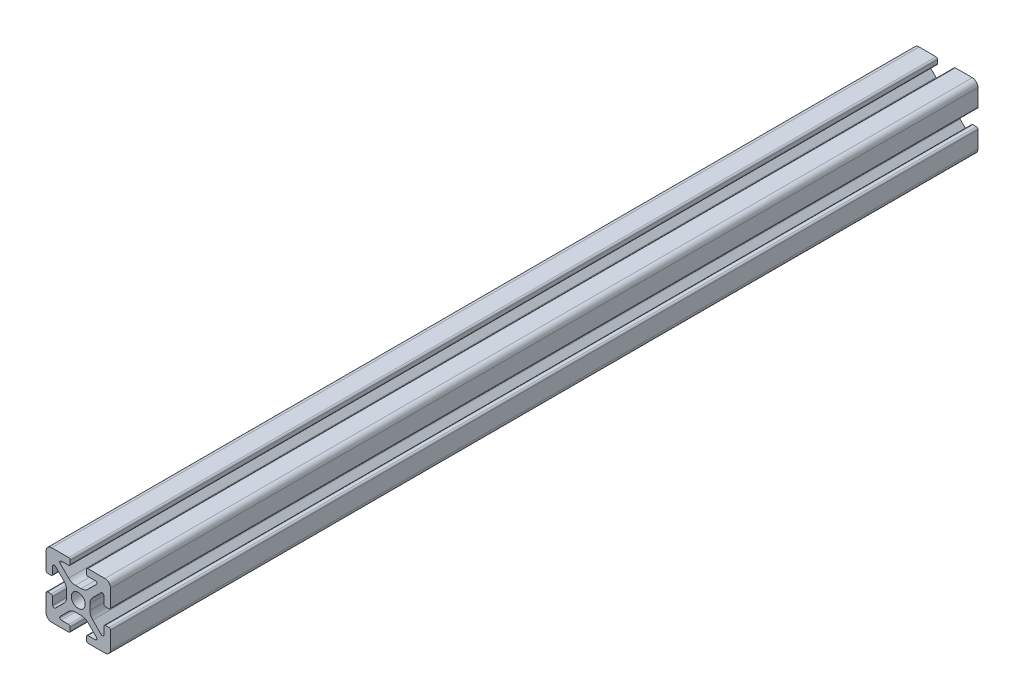
SolidWorks part; units mm, degrees
material "1060 Alloy"
ref_plane "Front Plane" through (0, 0, 0) normal (0, 0, 1) x (1, 0, 0)
ref_plane "Top Plane" through (0, 0, 0) normal (0, 1, 0) x (1, 0, 0)
ref_plane "Right Plane" through (0, 0, 0) normal (1, 0, 0) x (0, 0, -1)
sketch "Sketch2" plane through (0, 0, 0) normal (0, 0, 1) x (1, 0, 0)
  line L0 (0, 10) -> (0, -10) construction
  line L1 (-10, 0) -> (10, 0) construction
  line L2 (2.5, -10) -> (10, -10)
  line L3 (10, -10) -> (10, -2.5)
  line L4 (2.5, -10) -> (2.5, -7.9246)
  line L5 (2.5, -7.9246) -> (6.4571, -7.9246)
  line L6 (6.4571, -7.9246) -> (2.1325, -3.6)
  line L7 (0, 0) -> (10, -10) construction
  line L8 (10, -2.5) -> (7.9246, -2.5)
  line L9 (7.9246, -2.5) -> (7.9246, -6.4571)
  line L10 (7.9246, -6.4571) -> (3.6, -2.1325)
  line L11 (5.7623, -4.2948) -> (4.2948, -5.7623) construction
  circle A0 centre (0, 0) radius 2.15
  arc A1 (5.25, -7.9246) -> (5.6036, -7.0711) centre (5.25, -7.4246) ccw construction
  point P8 (0, -3.6)
  point P16 (5.0286, -5.0286)
  dimension "Center Hole Diameter" = 4.3
  dimension "D3" = 0.5
  dimension "Rail Height" = 20
  dimension "Rail Width" = 20
  dimension "T-Slot Width" = 5
  dimension "Slot Depth" = 6.4
  dimension "Slot Inner Width" = 11.5
sketch "Sketch3" plane through (0, 0, 0) normal (1, 0, 0) x (0, 0, -1)
  line L0 (-135.5, -10) -> (135.5, -10) construction
  line L1 (-110.1, 0) -> (110.1, 0) construction
  line L2 (0, 10) -> (0, -10) construction
  line L3 (0, 10) -> (0, -10) construction
  point P6 (-110.1, 0)
  point P8 (110.1, 0)
  dimension "Length" = 271
  dimension "D1" = 25.4
sketch "Sketch4" plane through (0, 0, 0) normal (0, 0, 1) x (1, 0, 0)
  line L0 (3, -10) -> (8.25, -10)
  line L1 (2.5, -10) -> (10, -10) construction
  line L2 (2.5, -10) -> (2.5, -7.9246) construction
  line L3 (2.5, -7.9246) -> (6.4571, -7.9246) construction
  line L4 (2.5, -8.4246) -> (2.5, -9.5)
  line L5 (3, -7.9246) -> (5.25, -7.9246)
  line L6 (0, -3.6) -> (0.8898, -3.6)
  line L7 (6.4571, -7.9246) -> (2.1325, -3.6) construction
  line L8 (3.0112, -4.4787) -> (5.6036, -7.0711)
  line L9 (10, -10) -> (10, -2.5) construction
  line L10 (7.9246, -6.4571) -> (3.6, -2.1325) construction
  line L11 (7.9246, -2.5) -> (7.9246, -6.4571) construction
  line L12 (7.9246, -5.25) -> (7.9246, -3)
  line L13 (10, -2.5) -> (7.9246, -2.5) construction
  line L14 (8.4246, -2.5) -> (9.5, -2.5)
  line L15 (10, -3) -> (10, -8.25)
  line L16 (7.0711, -5.6036) -> (4.4787, -3.0112)
  line L17 (3.6, 0) -> (3.6, -0.8898)
  line L18 (-10, 0) -> (10, 0) construction
  line L19 (0, -3.6) -> (0, -2.15)
  line L20 (0, 10) -> (0, -10) construction
  line L21 (3.6, 0) -> (2.15, 0)
  arc A0 (2.5, -9.5) -> (3, -10) centre (3, -9.5) ccw
  arc A1 (5.25, -7.9246) -> (5.6036, -7.0711) centre (5.25, -7.4246) ccw construction
  arc A2 (2.5, -8.4246) -> (3, -7.9246) centre (3, -8.4246) cw
  arc A3 (5.25, -7.9246) -> (5.6036, -7.0711) centre (5.25, -7.4246) ccw
  arc A4 (0.8898, -3.6) -> (3.0112, -4.4787) centre (0.8898, -6.6) cw
  arc A5 (8.25, -10) -> (10, -8.25) centre (8.25, -8.25) ccw
  arc A6 (7.0711, -5.6036) -> (7.9246, -5.25) centre (7.4246, -5.25) ccw
  arc A7 (7.9246, -3) -> (8.4246, -2.5) centre (8.4246, -3) cw
  arc A8 (9.5, -2.5) -> (10, -3) centre (9.5, -3) cw
  arc A9 (4.4787, -3.0112) -> (3.6, -0.8898) centre (6.6, -0.8898) cw
  circle A10 centre (0, 0) radius 2.15 construction
  arc A11 (0, -2.15) -> (2.15, 0) centre (0, 0) ccw
  dimension "D1" = 1.75
  dimension "D2" = 3
extrude "Boss-Extrude1" add sketch "Sketch4" along normal mid plane 271
mirror "Mirror1" about plane through (0, 0, 0) normal (1, 0, 0) of bodies 134
mirror "Mirror2" about plane through (0, 0, 0) normal (0, 1, 0) of bodies 135
sketch "Sketch5" plane through (0, 0, 135.5) normal (0, 0, 1) x (1, 0, 0)
  line L1 (-13.9539, 12.3566) -> (13.8334, 12.3566)
  line L2 (-13.9539, 12.3566) -> (-13.9539, -13.6827)
  line L3 (-13.9539, -13.6827) -> (13.8334, -13.6827)
  line L4 (13.8334, 12.3566) -> (13.8334, -13.6827)
extrude "Cut-Extrude1" cut sketch "Sketch5" against normal blind 2.4
equation "\"D3@Sketch2\"=\"T-Slot Width@Sketch2\"*0.1"
equation "\"D1@Sketch4\"=\"D3@Sketch2\"*3.5"
equation "\"D2@Sketch4\"=\"D3@Sketch2\"*6"
equation "\"D1@Boss-Extrude1\"=\"Length@Sketch3\""
